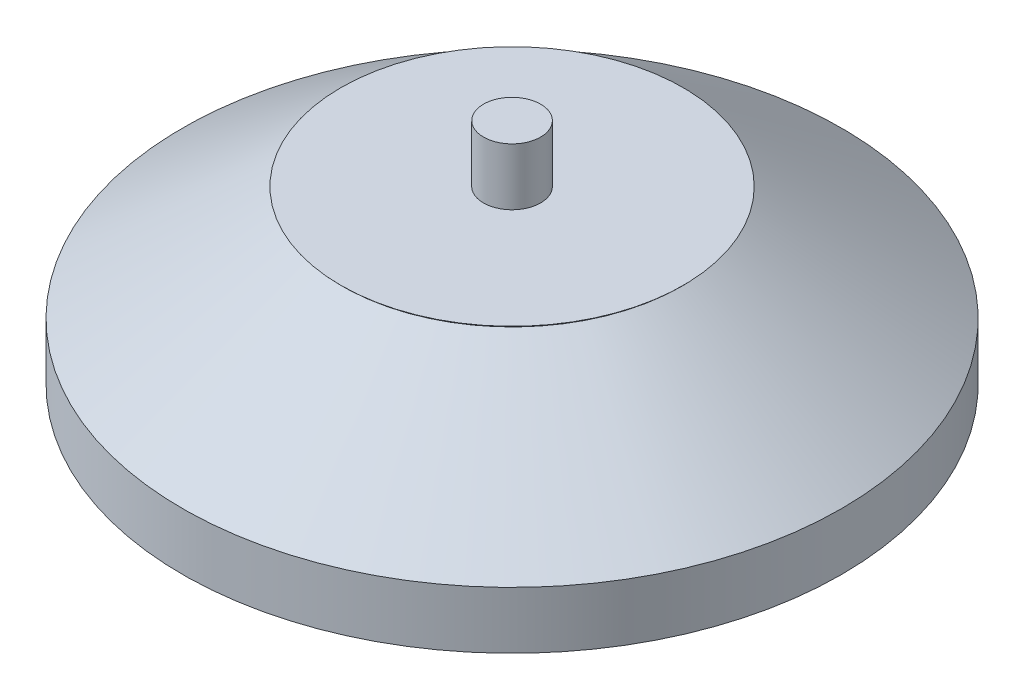
SolidWorks part; units mm, degrees
ref_plane "Front Plane" through (0, 0, 0) normal (0, 0, 1) x (1, 0, 0)
ref_plane "Top Plane" through (0, 0, 0) normal (0, 1, 0) x (1, 0, 0)
ref_plane "Right Plane" through (0, 0, 0) normal (1, 0, 0) x (0, 0, -1)
sketch "Sketch1" plane through (0, 0, 0) normal (0, 0, 1) x (1, 0, 0)
  line L0 (-42.6436, 0) -> (41.8718, 0) construction
  line L3 (0.389, -0.0678) -> (-5.2268, -4)
  line L4 (0.389, -0.0678) -> (-5.6788, 6)
  line L7 (6.3212, 11.0477) -> (6.3212, -9.609) construction
  line L12 (-5.2268, -4) -> (6.3212, -4)
  line L13 (6.3212, -4) -> (6.3212, 6)
  line L14 (6.3212, 6) -> (-5.6788, 6)
  point P3 (-0.3859, 0)
  point P4 (-16.1486, 15.7627)
  point P6 (-17.3053, -11.8471)
  point P7 (-17.0185, -12.2567)
  point P8 (-15.795, 16.1162)
  dimension "D6" = 12
revolve "Revolve1" add sketch "Sketch1" angle 360 about L7
scale "Scale1" [suppressed]
split "Split2" trim tools "Top Plane" bodies to split 101 resulting bodies 117 118
sketch "Sketch11" plane through (0, 6, 0) normal (0, 1, 0) x (1, 0, 0)
  circle A0 centre (6.3212, 0) radius 12 construction
  circle A1 centre (6.3212, 0) radius 12
extrude "Boss-Extrude3" add sketch "Sketch11" along normal blind 2
delete or keep bodies "Body-Delete/Keep 3" type delete bodies bodies 119
sketch "Sketch13" plane through (0, -4, 0) normal (0, -1, 0) x (1, 0, 0)
  circle A0 centre (6.3212, 0) radius 11.548 construction
  circle A1 centre (6.3212, 0) radius 11.548
extrude "Boss-Extrude4" add sketch "Sketch13" along normal blind 2
sketch "Sketch14" plane through (0, 0, 0) normal (0, 1, 0) x (1, 0, 0)
  line L0 (-3.3, 0) -> (3.3, 0) construction
  circle A0 centre (6.3212, 0) radius 1
  circle A1 centre (6.3212, 0) radius 6 construction
  dimension "D1" = 2
extrude "Boss-Extrude5" add sketch "Sketch14" along normal blind 2
